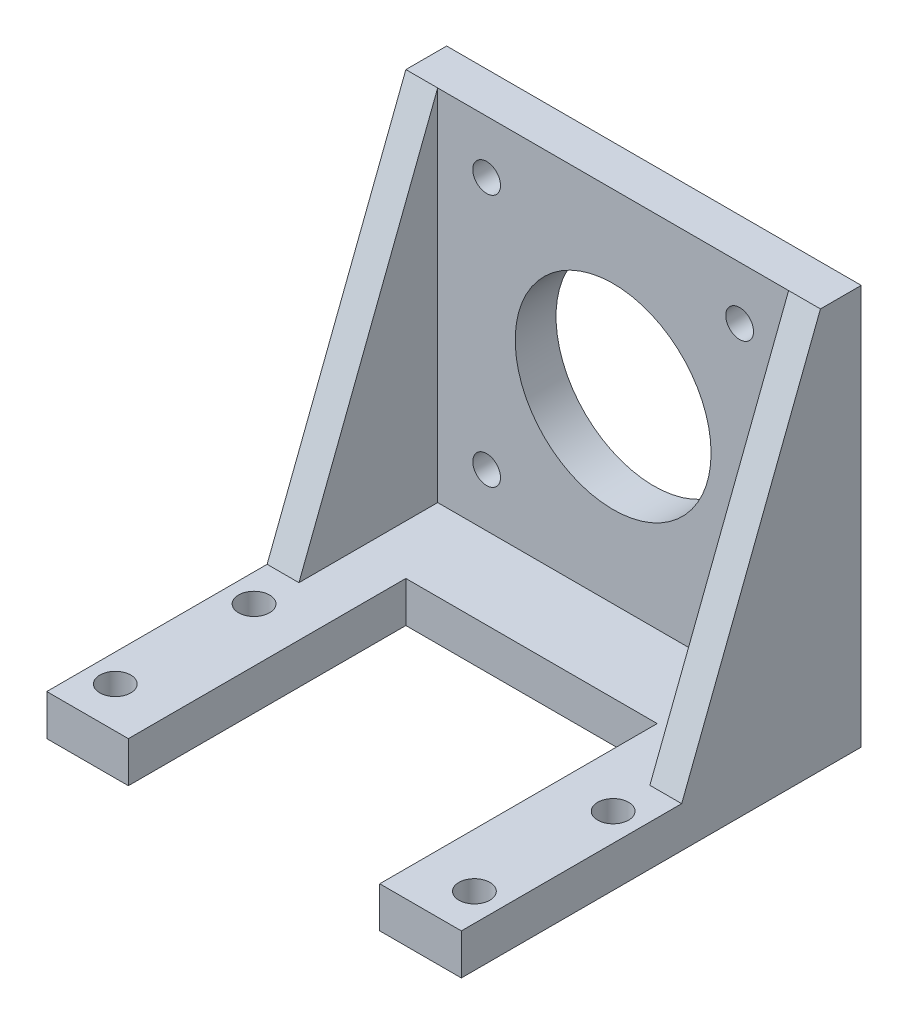
SolidWorks part; units mm, degrees
ref_plane "Front Plane" through (0, 0, 0) normal (0, 0, 1) x (1, 0, 0)
ref_plane "Top Plane" through (0, 0, 0) normal (0, 1, 0) x (1, 0, 0)
ref_plane "Right Plane" through (0, 0, 0) normal (1, 0, 0) x (0, 0, -1)
sketch "Sketch1" plane through (0, 0, 0) normal (1, 0, 0) x (0, 0, -1)
  line L0 (-22, -22) -> (-22, -27)
  line L3 (-22, -27) -> (27, -27)
  line L4 (27, 22) -> (27, -27)
  line L9 (-22, -22) -> (22, -22)
  line L10 (22, 22) -> (22, -22)
  line L11 (-0.1286, 0.1286) -> (22, -22) construction
  line L12 (-22, -22) -> (22, 22) construction
  line L13 (22, 22) -> (27, 22)
  point P0 (0, 0)
  point P2 (0, 0)
  point P3 (28.4872, -25.6728)
  point P4 (27.08, -27.08)
  point P6 (0, 0)
  dimension "D1" = 5
  dimension "D2" = 44
extrude "Boss-Extrude1" add sketch "Sketch1" along normal mid plane 50.8
sketch "Sketch2" plane through (0, 0, -22) normal (0, 0, 1) x (1, 0, 0)
  line L1 (-15.5, -15.5) -> (15.5, -15.5) construction
  line L2 (-15.5, -15.5) -> (-15.5, 15.5) construction
  line L3 (-15.5, 15.5) -> (15.5, 15.5) construction
  line L4 (15.5, -15.5) -> (15.5, 15.5) construction
  line L5 (-15.5, -15.5) -> (15.5, 15.5) construction
  line L6 (-15.5, 15.5) -> (15.5, -15.5) construction
  circle A0 centre (-15.5, 15.5) radius 1.7
  circle A1 centre (15.5, 15.5) radius 1.7
  circle A2 centre (15.5, -15.5) radius 1.7
  circle A3 centre (-15.5, -15.5) radius 1.7
  circle A4 centre (0, 0) radius 12
  point P0 (0, 0)
  dimension "D2" = 3.4
  dimension "D3" = 24
  dimension "D1" = 31
extrude "Cut-Extrude1" cut sketch "Sketch2" against normal through all
sketch "Sketch4" plane through (0, -22, 0) normal (0, 1, 0) x (1, 0, 0)
  line L0 (25.4, -22) -> (-25.4, -22) construction
  line L1 (-15.4, -22) -> (15.4, -22)
  line L2 (-15.4, -22) -> (-15.4, 12)
  line L3 (-15.4, 12) -> (15.4, 12)
  line L4 (15.4, -22) -> (15.4, 12)
  line L5 (-15.4, -22) -> (15.4, 12) construction
  line L6 (-15.4, 12) -> (15.4, -22) construction
  line L7 (25.4, 22) -> (-25.4, 22) construction
  line L8 (-25.4, 22) -> (-25.4, -22) construction
  point P0 (0, -5)
  point P7 (0, 0)
  dimension "D1" = 10
  dimension "D2" = 10
extrude "Cut-Extrude2" cut sketch "Sketch4" against normal through all
sketch "Sketch5" plane through (0, -22, 0) normal (0, 1, 0) x (1, 0, 0)
  line L1 (22, -17) -> (-22, -17) construction
  line L2 (22, -17) -> (22, 0) construction
  line L3 (22, 0) -> (-22, 0) construction
  line L4 (-22, -17) -> (-22, 0) construction
  line L5 (22, -17) -> (-22, 0) construction
  line L6 (22, 0) -> (-22, -17) construction
  line L8 (-15.4, -22) -> (-25.4, -22) construction
  line L9 (25.4, 22) -> (-25.4, 22) construction
  circle A0 centre (-22, 0) radius 1.8986
  circle A1 centre (22, 0) radius 1.8986
  circle A2 centre (22, -17) radius 1.8986
  circle A3 centre (-22, -17) radius 1.8986
  point P0 (0, -8.5)
  dimension "D4" = 3.7973
  dimension "D1" = 44
  dimension "D2" = 5
  dimension "D3" = 22
extrude "Cut-Extrude3" cut sketch "Sketch5" against normal through all
sketch "Sketch6" plane through (25.4, 0, 0) normal (1, 0, 0) x (0, 0, -1)
  line L0 (5, -22) -> (22, 22)
  line L1 (22, -22) -> (-22, -22) construction
  line L2 (22, 22) -> (22, -22) construction
  line L3 (22, 22) -> (22, -22)
  line L4 (22, -22) -> (5, -22)
  line L5 (1.8986, -22) -> (-1.8986, -22) construction
  line L6 (1.8986, -22) -> (-1.8986, -22)
  line L7 (0, -22) -> (0, 49978) construction
  point P12 (0, -22)
  point P13 (0, 0)
  line M7 (22, 22) -> (22, -22)
  line M8 (22, -22) -> (-22, -22)
  dimension "D1" = 5
extrude "Boss-Extrude2" add sketch "Sketch6" against normal offset from surface (3.9 mm away) 21.5 contours L0 M8 M7 up to plane "Right Plane"
mirror "Mirror1" about plane through (0, 0, 0) normal (1, 0, 0) of "Boss-Extrude2"
